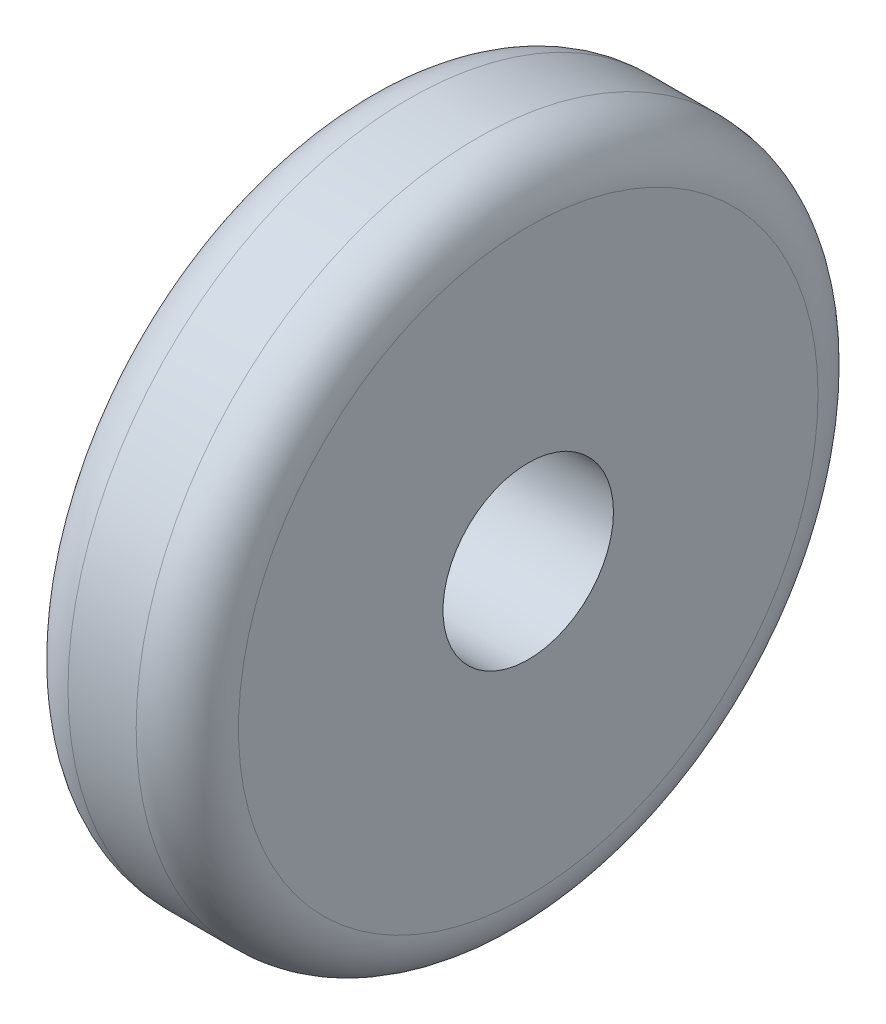
SolidWorks part; units mm, degrees
material "BUTYL"
ref_plane "Front Plane" through (0, 0, 0) normal (0, 0, 1) x (1, 0, 0)
ref_plane "Top Plane" through (0, 0, 0) normal (0, 1, 0) x (1, 0, 0)
ref_plane "Right Plane" through (0, 0, 0) normal (1, 0, 0) x (0, 0, -1)
sketch "Sketch1" plane through (0, 0, 0) normal (1, 0, 0) x (0, 0, -1)
  circle A0 centre (0, 0) radius 5
  circle A1 centre (0, 0) radius 20
  dimension "D1" = 15
  dimension "D2" = 10
extrude "Boss-Extrude1" add sketch "Sketch1" along normal mid plane 10
fillet "Fillet1" radius 3 2 edges at (-5, 0, -20) (5, 0, -20)
